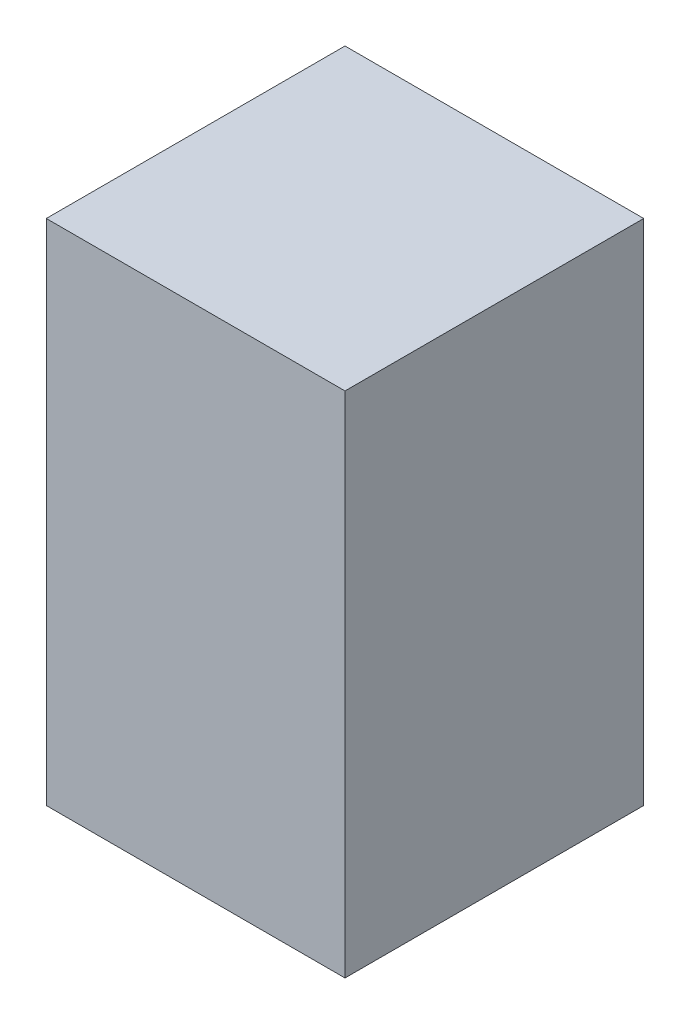
SolidWorks part; units mm, degrees
ref_plane "Front Plane" through (0, 0, 0) normal (0, 0, 1) x (1, 0, 0)
ref_plane "Top Plane" through (0, 0, 0) normal (0, 1, 0) x (1, 0, 0)
ref_plane "Right Plane" through (0, 0, 0) normal (1, 0, 0) x (0, 0, -1)
sketch "Sketch1" plane through (0, 0, 0) normal (0, 1, 0) x (1, 0, 0)
  line L1 (-50, -50) -> (50, -50)
  line L2 (-50, -50) -> (-50, 50)
  line L3 (-50, 50) -> (50, 50)
  line L4 (50, -50) -> (50, 50)
  line L5 (-50, -50) -> (50, 50) construction
  line L6 (-50, 50) -> (50, -50) construction
  point P0 (0, 0)
  dimension "D1" = 100
  dimension "D2" = 100
extrude "Boss-Extrude1" add sketch "Sketch1" along normal blind 170.2
sketch "Sketch2" plane through (0, 0, 0) normal (0, -1, 0) x (1, 0, 0)
  circle A0 centre (0, 0) radius 38.6297
extrude "Cut-Extrude1" cut sketch "Sketch2" against normal blind 39.2
sketch "Sketch3" plane through (0, 39.2, 0) normal (0, -1, 0) x (1, 0, 0)
  circle A0 centre (0, 0) radius 26.3668
extrude "Boss-Extrude2" add sketch "Sketch3" along normal blind 39.2
